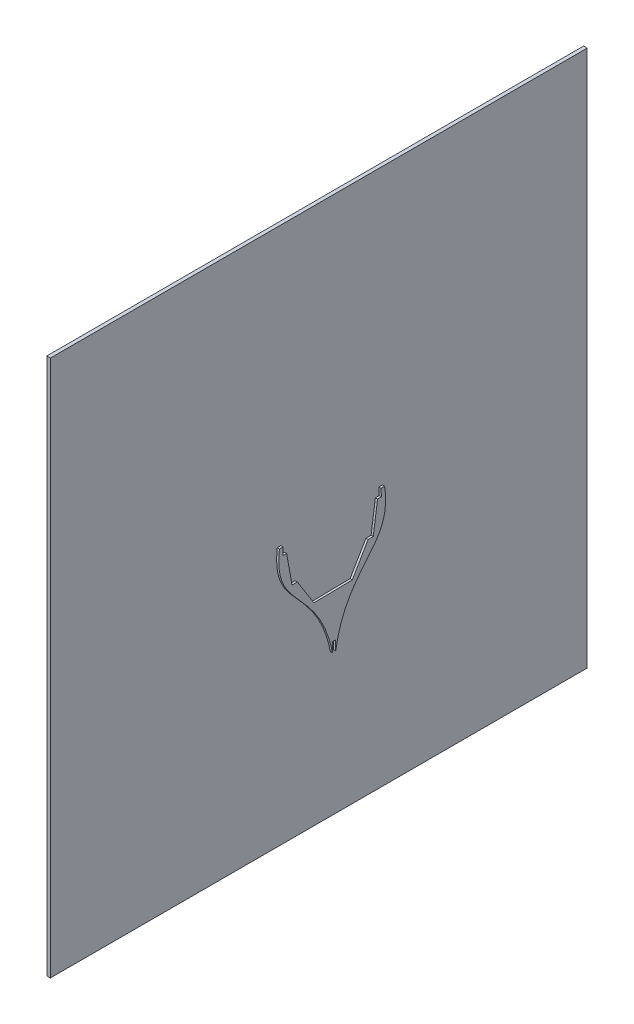
SolidWorks part; units mm, degrees
ref_plane "Plan de face" through (0, 0, 0) normal (0, 0, 1) x (1, 0, 0)
ref_plane "Plan de dessus" through (0, 0, 0) normal (0, 1, 0) x (1, 0, 0)
ref_plane "Plan de droite" through (0, 0, 0) normal (1, 0, 0) x (0, 0, -1)
sketch "Esquisse1" plane through (0, 0, 0) normal (0, 0, 1) x (1, 0, 0)
  point P0 (-20, 0)
  dimension "D1" = 20
sketch3d "Esquisse3D1"
  line L1 (-20, 1121.2893, 777.275) -> (-20, 1121.2893, -722.725)
  line L2 (-20, 1121.2893, 777.275) -> (-20, -378.7107, 777.275)
  line L3 (-20, -378.7107, 777.275) -> (-20, -378.7107, -722.725)
  line L4 (-20, 1121.2893, -722.725) -> (-20, -378.7107, -722.725)
  dimension "D1" = 1500
  dimension "D2" = 1500
extrude "Boss.-Extru.2" add sketch "Esquisse3D1" along direction (1, 0, 0) on the side of the normal blind 10 contours L2 L1 L4 L3
sketch "Esquisse4" plane through (-10, 0, 0) normal (1, 0, 0) x (0, 0, -1)
  line L0 (0, 0) -> (-7.701, 425.1082) construction
  line L1 (169.3944, 339.9131) -> (-188.5193, 333.4294) construction
  line L2 (-187.2006, 249.23) -> (169.0622, 255.6839) construction
  line L3 (-144.268, 175.2448) -> (126.4811, 180.1495) construction
sketch "Esquisse5" plane through (0, 0, 0) normal (1, 0, 0) x (0, 0, -1)
  line L0 (-7.701, 425.1082) -> (0, 0) construction
  line L2 (0, 0) -> (3.955, 18.2202) construction
  line L3 (3.955, 18.2202) -> (8.4841, 238.1393) construction
  line L4 (8.4841, 238.1393) -> (167.961, 180.8474) construction
  line L5 (167.961, 180.8474) -> (140.4761, 360.5035) construction
  line L8 (140.4761, 360.5035) -> (130.4761, 360.3223)
  line L9 (130.4761, 360.3223) -> (131.6577, 339.2295)
  line L10 (169.3944, 339.9131) -> (-188.5193, 333.4294) construction
  line L11 (131.6577, 339.2295) -> (120.888, 339.0344)
  line L12 (120.888, 339.0344) -> (108.8733, 254.5935)
  line L13 (-187.2006, 249.23) -> (169.0622, 255.6839) construction
  line L14 (108.8733, 254.5935) -> (94.3454, 254.3304)
  line L15 (94.3454, 254.3304) -> (50.3215, 178.7698)
  line L16 (-144.268, 175.2448) -> (126.4811, 180.1495) construction
  line L17 (50.3215, 178.7698) -> (-56.7633, 176.8299)
  line L18 (0, 0) -> (-4.6123, 18.065) construction
  line L19 (-4.6123, 18.065) -> (-17.1037, 237.6758) construction
  line L20 (-17.1037, 237.6758) -> (-174.4008, 174.6454) construction
  line L21 (-174.4008, 174.6454) -> (-153.441, 355.1791) construction
  line L22 (-103.4951, 250.7464) -> (-56.7633, 176.8299)
  line L23 (-118.023, 250.4832) -> (-103.4951, 250.7464)
  line L24 (-133.0881, 334.4335) -> (-118.023, 250.4832)
  line L25 (-143.8578, 334.2384) -> (-133.0881, 334.4335)
  line L26 (-143.441, 355.3602) -> (-143.8578, 334.2384)
  line L27 (-153.441, 355.1791) -> (-143.441, 355.3602)
  spline S0 degree 4 poles (0, 0) (3.955, 18.2202) (8.4841, 238.1393) (167.961, 180.8474) (140.4761, 360.5035) knots 0 0 0 0 0 1 1 1 1 1
  spline S1 degree 4 poles (0, 0) (-4.6123, 18.065) (-17.1037, 237.6758) (-174.4008, 174.6454) (-153.441, 355.1791) knots 0 0 0 0 0 1 1 1 1 1
  point P30 (-3.2209, 177.7999)
  dimension "D1" = 10
extrude "Boss.-Extru.3" add sketch "Esquisse5" along normal blind 6 separate body
sketch "Esquisse6" plane through (6, 0, 0) normal (1, 0, 0) x (0, 0, -1)
  line L0 (-5.0445, 29.9772) -> (-5.5336, 56.9772)
  line L1 (-5.5336, 56.9772) -> (3.4664, 57.1402)
  line L2 (3.4664, 57.1402) -> (3.9555, 30.1402)
  line L3 (3.9555, 30.1402) -> (117.0633, -47.527)
  line L4 (117.0633, -47.527) -> (-85.2277, -65.22)
  line L5 (-85.2277, -65.22) -> (-5.0445, 29.9772)
  line L6 (-5.0445, 29.9772) -> (3.9555, 30.1402) construction
  line L7 (-144.268, 175.2448) -> (126.4811, 180.1495) construction
  spline S0 degree 4 poles (-153.441, 355.1791) (-174.4008, 174.6454) (-17.1037, 237.6758) (-4.6123, 18.065) (0, 0) knots 0 0 0 0 0 1 1 1 1 1 construction
  spline S1 degree 4 poles (0, 0) (3.955, 18.2202) (8.4841, 238.1393) (167.961, 180.8474) (140.4761, 360.5035) knots 0 0 0 0 0 1 1 1 1 1 construction
  dimension "D1" = 9
  dimension "D2" = 27
extrude "Enlèv. mat.-Extru.1" cut sketch "Esquisse6" against normal blind 6
